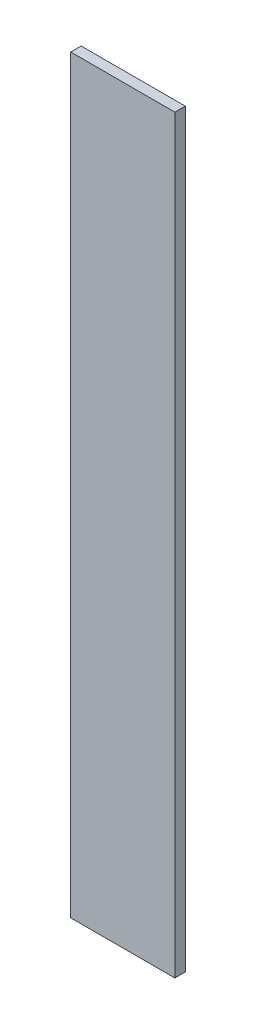
SolidWorks part; units mm, degrees
material "Acrylic (Medium-high impact)"
ref_plane "Front Plane" through (0, 0, 0) normal (0, 0, 1) x (1, 0, 0)
ref_plane "Top Plane" through (0, 0, 0) normal (0, 1, 0) x (1, 0, 0)
ref_plane "Right Plane" through (0, 0, 0) normal (1, 0, 0) x (0, 0, -1)
sketch "Sketch1" plane through (0, 0, 0) normal (0, 1, 0) x (1, 0, 0)
  line L1 (15.875, -1.5875) -> (-15.875, -1.5875)
  line L2 (15.875, -1.5875) -> (15.875, 1.5875)
  line L3 (15.875, 1.5875) -> (-15.875, 1.5875)
  line L4 (-15.875, -1.5875) -> (-15.875, 1.5875)
  line L5 (15.875, -1.5875) -> (-15.875, 1.5875) construction
  line L6 (15.875, 1.5875) -> (-15.875, -1.5875) construction
  point P0 (0, 0)
  dimension "D1" = 3.175
  dimension "D2" = 31.75
extrude "Boss-Extrude1" add sketch "Sketch1" along normal blind 228.6
